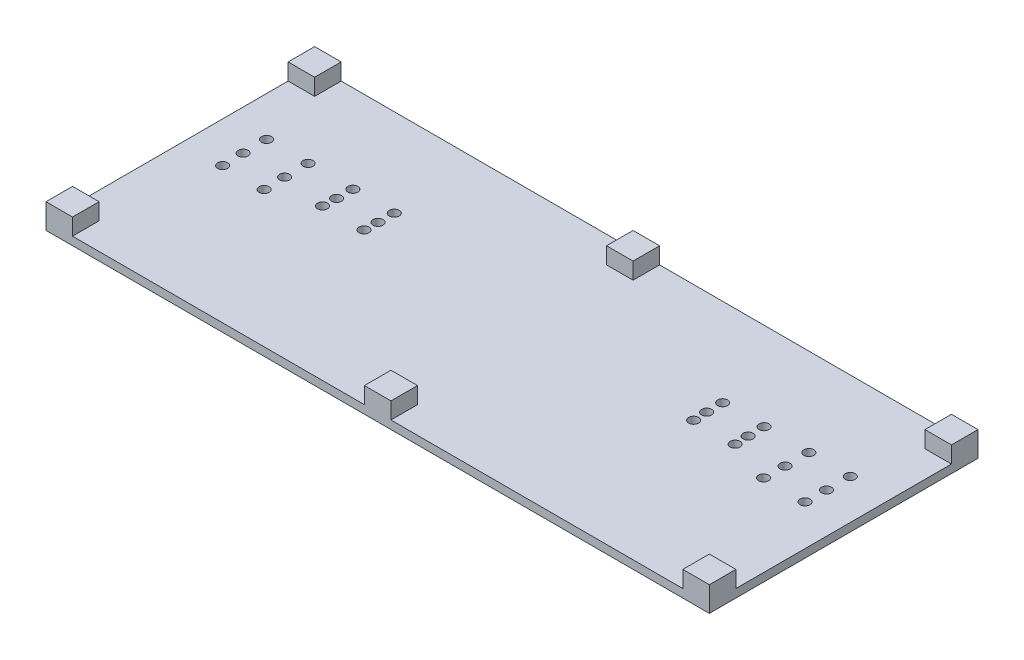
SolidWorks part; units mm, degrees
material "PE High Density"
ref_plane "Front Plane" through (0, 0, 0) normal (0, 0, 1) x (1, 0, 0)
ref_plane "Top Plane" through (0, 0, 0) normal (0, 1, 0) x (1, 0, 0)
ref_plane "Right Plane" through (0, 0, 0) normal (1, 0, 0) x (0, 0, -1)
sketch "Sketch1" plane through (0, 0, 0) normal (0, 1, 0) x (1, 0, 0)
  line L0 (-2067.6751, 0) -> (101316.0801, 0) construction
  line L1 (0, 40.5) -> (100, 40.5)
  line L2 (0, 40.5) -> (0, -40.5)
  line L3 (0, -40.5) -> (100, -40.5)
  line L4 (100, 40.5) -> (100, -40.5)
  line L5 (0, -2067.6751) -> (0, 101316.0801) construction
  dimension "D1" = 100
  dimension "D2" = 81
  dimension "D3" = 40.5
extrude "Boss-Extrude1" add sketch "Sketch1" against normal blind 2.5
sketch "Sketch3" plane through (0, 0, 0) normal (0, 1, 0) x (1, 0, 0)
  line L0 (-1000, 0) -> (49000, 0) construction
  line L1 (0, 40.5) -> (0, -40.5) construction
  line L2 (0, 40.5) -> (0, -40.5) construction
  line L3 (100, 40.5) -> (0, 40.5) construction
  line L4 (75, -986.4003) -> (75, 49013.5997) construction
  line L5 (88, 14) -> (62, 14) construction
  line L6 (62.1975, 16.2574) -> (87.8025, 11.7426) construction
  line L7 (87.9505, 12.867) -> (62.0495, 15.133) construction
  line L8 (62.0495, 9.1526) -> (87.9505, 6.8866) construction
  line L9 (62.1975, 5.0738) -> (87.8025, 0.559) construction
  line L10 (62, -986) -> (62, 49014) construction
  line L11 (88, -986) -> (88, 49014) construction
  line L12 (-938, 14) -> (49062, 14) construction
  line L13 (-937.9505, 9.1526) -> (49062.0495, 9.1526) construction
  line L14 (-937.8025, 5.0738) -> (49062.1975, 5.0738) construction
  line L15 (-912.1975, 0.559) -> (49087.8025, 0.559) construction
  line L16 (-912.0495, 6.8866) -> (49087.9505, 6.8866) construction
  line L17 (62.5, -986) -> (62.5, 49014) construction
  line L18 (75.4505, 6.8866) -> (49.5495, 9.1526) construction
  line L19 (49.6975, 5.0738) -> (75.3025, 0.559) construction
  circle A0 centre (88, 14) radius 1.5
  circle A2 centre (62, 14) radius 1.5
  circle A3 centre (62.0495, 9.1526) radius 1.5
  circle A4 centre (87.9505, 6.8866) radius 1.5
  circle A5 centre (62.1975, 5.0738) radius 1.5
  circle A6 centre (87.8025, 0.559) radius 1.5
  circle A7 centre (49.5, 14) radius 1.5
  circle A8 centre (75.5, 14) radius 1.5
  circle A9 centre (49.5495, 9.1526) radius 1.5
  circle A10 centre (75.4505, 6.8866) radius 1.5
  circle A11 centre (49.6975, 5.0738) radius 1.5
  circle A12 centre (75.3025, 0.559) radius 1.5
  point P8 (75, 14)
  point P15 (75, 14)
  point P18 (87.9505, 12.867)
  point P19 (87.8025, 11.7426)
  point P20 (88, 14)
  point P24 (75, 2.8164)
  point P31 (75, 8.0196)
  point P59 (62.5, 8.0196)
  point P61 (62.5, 2.8164)
  dimension "D1" = 13
  dimension "D3" = 75
  dimension "D4" = 3
  dimension "D7" = 26
  dimension "D10" = 26
  dimension "D11" = 26
  dimension "D2" = 26.5
  dimension "D5" = 26
  dimension "D6" = 10
  dimension "D8" = 5
  dimension "D9" = 26
  dimension "D12" = 26
  dimension "D13" = 26
  dimension "D14" = 13
  dimension "D15" = 62.5
extrude "Cut-Extrude1" cut sketch "Sketch3" against normal through all
sketch "Sketch4" plane through (0, 0, 0) normal (0, 1, 0) x (1, 0, 0)
  line L6 (-1000, 0) -> (49000, 0) construction
  line L7 (100, -40.5) -> (92, -40.5)
  line L8 (100, -40.5) -> (100, -32.5)
  line L9 (100, -32.5) -> (92, -32.5)
  line L10 (92, -40.5) -> (92, -32.5)
  line L11 (100, 32.5) -> (92, 32.5)
  line L12 (92, 40.5) -> (92, 32.5)
  line L13 (100, 40.5) -> (92, 40.5)
  line L14 (100, 40.5) -> (100, 32.5)
  line L15 (0, -32.5) -> (4, -32.5)
  line L16 (0, 40.5) -> (4, 40.5)
  line L17 (0, 40.5) -> (0, 32.5)
  line L18 (0, 32.5) -> (4, 32.5)
  line L19 (4, 40.5) -> (4, 32.5)
  line L20 (4, -40.5) -> (4, -32.5)
  line L21 (0, -40.5) -> (4, -40.5)
  line L22 (0, -40.5) -> (0, -32.5)
extrude "Boss-Extrude2" add sketch "Sketch4" along normal blind 5
mirror "Mirror1" about plane through (0, 0, 0) normal (1, 0, 0) of "Boss-Extrude2", "Cut-Extrude1", "Boss-Extrude1"
